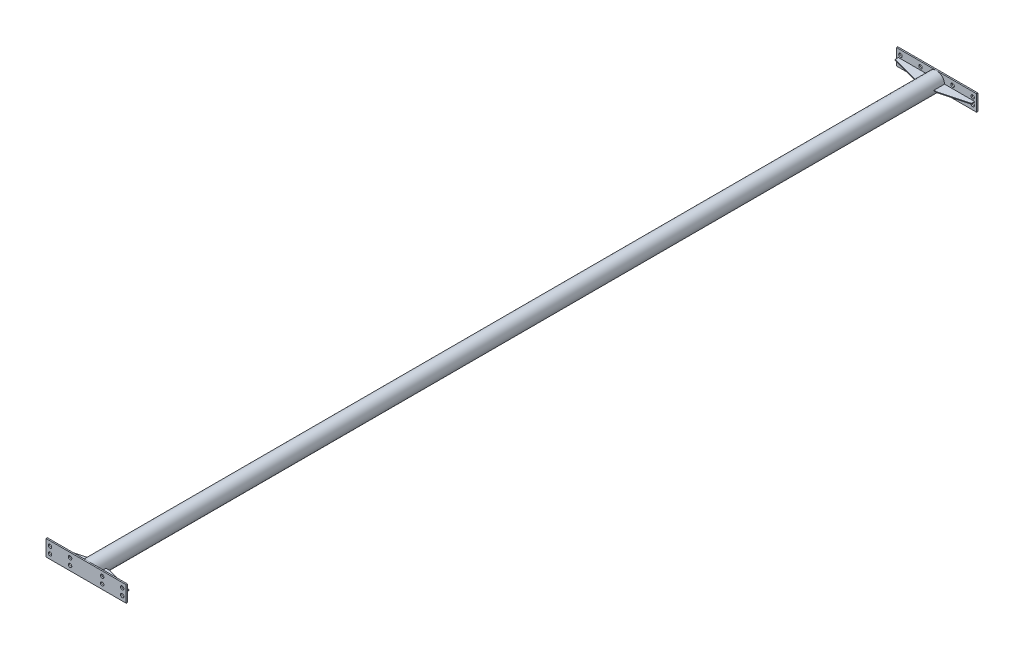
SolidWorks part; units mm, degrees
material "Plain Carbon Steel"
ref_plane "Front Plane" through (0, 0, 0) normal (0, 0, 1) x (1, 0, 0)
ref_plane "Top Plane" through (0, 0, 0) normal (0, 1, 0) x (1, 0, 0)
ref_plane "Right Plane" through (0, 0, 0) normal (1, 0, 0) x (0, 0, -1)
sketch "Sketch1" plane through (0, 0, 0) normal (0, 0, 1) x (1, 0, 0)
  line L1 (-300, -60) -> (300, -60)
  line L2 (-300, -60) -> (-300, 60)
  line L3 (-300, 60) -> (300, 60)
  line L4 (300, -60) -> (300, 60)
  line L5 (-300, -60) -> (300, 60) construction
  line L6 (-300, 60) -> (300, -60) construction
  point P0 (0, 0)
  dimension "D1" = 120
  dimension "D2" = 600
extrude "Boss-Extrude1" add sketch "Sketch1" along normal blind 10
sketch "Sketch2" plane through (0, 0, 10) normal (0, 0, 1) x (1, 0, 0)
  line L0 (300, 60) -> (-300, 60) construction
  circle A0 centre (0, 0) radius 60
extrude "Boss-Extrude2" add sketch "Sketch2" along normal blind 6350 separate body
sketch "Sketch4" plane through (0, 0, 0) normal (0, 1, 0) x (1, 0, 0)
  line L0 (285, -10) -> (285, -35)
  line L1 (300, -10) -> (-300, -10) construction
  line L2 (285, -35) -> (85, -88.5898)
  line L3 (85, -88.5898) -> (60, -88.5898)
  line L4 (60, -6360) -> (60, -10) construction
  line L5 (60, -88.5898) -> (60, -10)
  line L6 (60, -10) -> (285, -10)
  line L7 (300, -10) -> (300, 0) construction
  line L8 (0, 0) -> (0, 133.0079) construction
  line L9 (-60, -10) -> (-285, -10)
  line L10 (-60, -88.5898) -> (-60, -10)
  line L11 (-85, -88.5898) -> (-60, -88.5898)
  line L12 (-285, -35) -> (-85, -88.5898)
  line L13 (-285, -10) -> (-285, -35)
  dimension "D1" = 15
  dimension "D2" = 25
  dimension "D3" = 25
  dimension "D4" = 15
extrude "Boss-Extrude3" add sketch "Sketch4" along normal mid plane 5 separate body
ref_plane "Plane1" through (0, 0, 3185) normal (0, 0, -1) x (-1, 0, 0)
mirror "Mirror1" about plane through (0, 0, 3185) normal (0, 0, -1) of bodies 101 104 103
sketch "Sketch6" plane through (0, 0, 3185) normal (0, 0, -1) x (-1, 0, 0)
  line L0 (0, 0) -> (0, 169.6645) construction
  line L1 (-300, 60) -> (300, 60) construction
  line L2 (300, -60) -> (-300, -60) construction
  line L3 (300, 60) -> (300, -60) construction
  circle A0 centre (270, 25) radius 13
  circle A1 centre (270, -25) radius 13
  circle A2 centre (120, 25) radius 13
  circle A3 centre (120, -25) radius 13
  circle A4 centre (-120, -25) radius 13
  circle A5 centre (-120, 25) radius 13
  circle A6 centre (-270, -25) radius 13
  circle A7 centre (-270, 25) radius 13
  dimension "D1" = 26
  dimension "D2" = 35
  dimension "D3" = 35
  dimension "D4" = 150
  dimension "D5" = 30
extrude "Cut-Extrude1" cut sketch "Sketch6" against normal through all both and the other way through all
